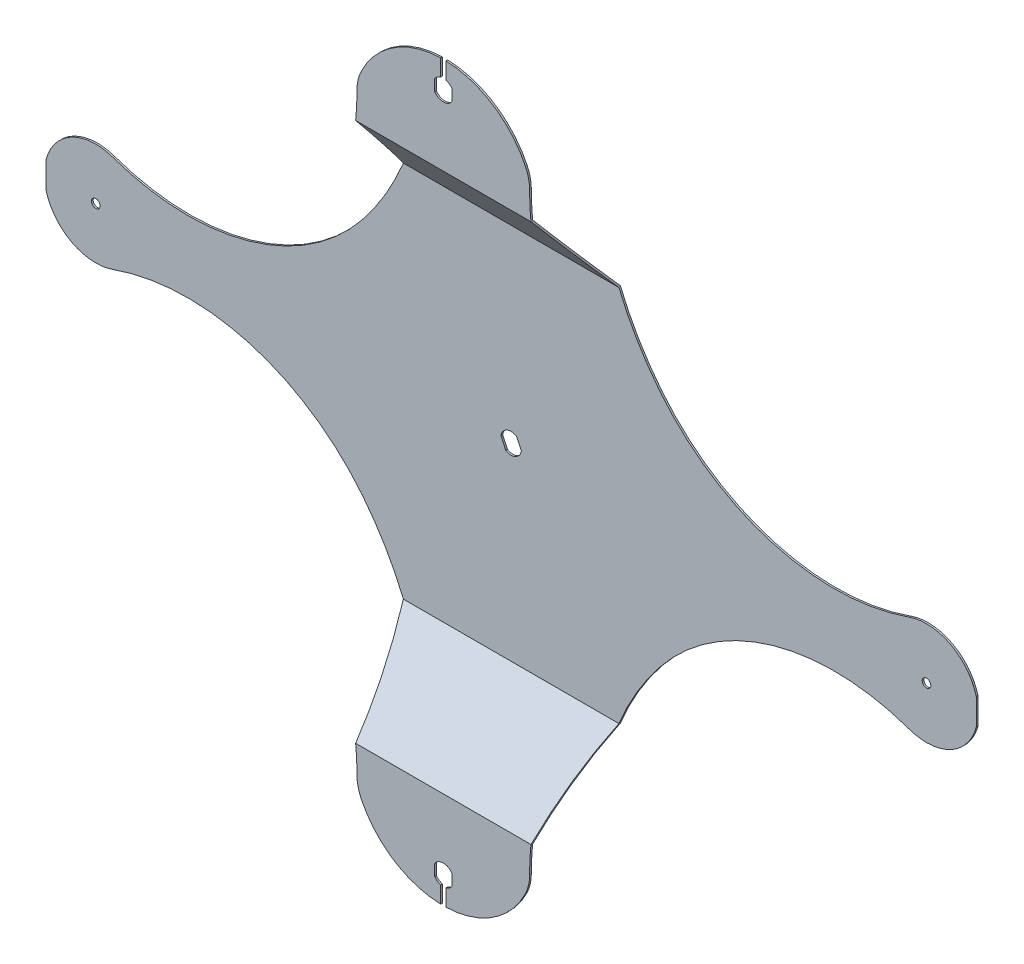
SolidWorks part; units mm, degrees
ref_plane "Alzado" through (0, 0, 0) normal (0, 0, 1) x (1, 0, 0)
ref_plane "Planta" through (0, 0, 0) normal (0, 1, 0) x (1, 0, 0)
ref_plane "Vista lateral" through (0, 0, 0) normal (1, 0, 0) x (0, 0, -1)
sketch "Croquis1" plane through (0, 0, 0) normal (1, 0, 0) x (0, 0, -1)
  line L0 (-18.5, -110) -> (-18.5, 110)
  line L1 (-18.5, 110) -> (-58.0314, 157.1117)
  line L2 (0, 0) -> (-82.8072, 0) construction
  line L3 (-58.0314, 157.1117) -> (-58.0314, 248)
  line L4 (-18.5, -110) -> (-58.0314, -157.1117)
  line L5 (-58.0314, -157.1117) -> (-58.0314, -248)
  line L6 (-57.0314, -157.4757) -> (-57.0314, -248)
  line L7 (-17.5, -110.364) -> (-57.0314, -157.4757)
  line L8 (-17.5, -110.364) -> (-17.5, 110.364)
  line L9 (-17.5, 110.364) -> (-57.0314, 157.4757)
  line L10 (-57.0314, 157.4757) -> (-57.0314, 248)
  line L11 (-58.0314, 248) -> (-57.0314, 248)
  line L12 (-58.0314, -248) -> (-57.0314, -248)
  point P9 (-18.5, 0)
  dimension "D1" = 18.5
  dimension "D2" = 50
  dimension "D3" = 61.5
  dimension "D4" = 110
  dimension "D5" = 496
  dimension "D6" = 1
extrude "Saliente-Extruir1" add sketch "Croquis1" along normal mid plane 542
sketch "Croquis2" plane through (0, 0, 0) normal (0, 0, 1) x (1, 0, 0)
  line L1 (0, 277.0309) -> (0, -277.0309) construction
  line L7 (-271, 213.5) -> (-1.5, 213.5) construction
  line L9 (-300.4496, 0) -> (300.4496, 0) construction
  line L10 (-271, 248) -> (-271, 157.1117) construction
  line L11 (271, 248) -> (271, 157.1117) construction
  line L12 (1.5, 213.5) -> (271, 213.5) construction
  line L13 (1.5, 198) -> (-1.5, 198)
  line L14 (1.5, 198) -> (1.5, 213.5)
  line L31 (-1.5, 198) -> (-1.5, 213.5)
  line L32 (1.5, -198) -> (-1.5, -198)
  line L33 (-1.5, -198) -> (-1.5, -213.5)
  line L34 (1.5, -198) -> (1.5, -213.5)
  line L36 (-300.4496, 277.0309) -> (300.4496, 277.0309)
  line L37 (-300.4496, 277.0309) -> (-300.4496, -277.0309)
  line L38 (-300.4496, -277.0309) -> (300.4496, -277.0309)
  line L39 (300.4496, 277.0309) -> (300.4496, -277.0309)
  line L40 (-300.4496, 277.0309) -> (300.4496, -277.0309) construction
  line L41 (-300.4496, -277.0309) -> (300.4496, 277.0309) construction
  circle A9 centre (0, 0) radius 247.5 construction
  arc A10 (-231.9486, 28.266) -> (-231.9486, -28.266) centre (-242, 0) ccw
  circle A11 centre (0, 0) radius 111.12 construction
  arc A13 (-1.5, 213.4272) -> (1.5, 213.4272) centre (0, 198) ccw construction
  arc A14 (-1.5, 213.5) -> (-47.85, 183.5) centre (0.0101, 160.3615) ccw
  circle A15 centre (0, 198) radius 50 construction
  arc A16 (-47.85, 183.5) -> (-50.3, 172.84) centre (-25.7251, 172.8035) ccw
  arc A17 (-50.3, 172.84) -> (-86.6952, 69.5097) centre (-215.8799, 173.0861) cw
  arc A18 (-231.9486, 28.266) -> (-86.6952, 69.5097) centre (-188.3108, 150.982) ccw
  arc A19 (-231.9486, -28.266) -> (-86.6952, -69.5097) centre (-188.3108, -150.982) cw
  arc A20 (-50.3, -172.84) -> (-86.6952, -69.5097) centre (-215.8799, -173.0861) ccw
  arc A21 (-47.85, -183.5) -> (-50.3, -172.84) centre (-25.7251, -172.8035) cw
  arc A22 (-1.5, -213.5) -> (-47.85, -183.5) centre (0.0101, -160.3615) cw
  arc A23 (47.85, 183.5) -> (50.3, 172.84) centre (25.7251, 172.8035) cw
  arc A24 (47.85, -183.5) -> (50.3, -172.84) centre (25.7251, -172.8035) ccw
  arc A25 (1.5, -213.5) -> (47.85, -183.5) centre (-0.0101, -160.3615) ccw
  arc A26 (50.3, -172.84) -> (86.6952, -69.5097) centre (215.8799, -173.0861) cw
  arc A27 (231.9486, -28.266) -> (86.6952, -69.5097) centre (188.3108, -150.982) ccw
  arc A28 (231.9486, 28.266) -> (231.9486, -28.266) centre (242, 0) cw
  arc A29 (231.9486, 28.266) -> (86.6952, 69.5097) centre (188.3108, 150.982) cw
  arc A30 (50.3, 172.84) -> (86.6952, 69.5097) centre (215.8799, 173.0861) ccw
  arc A31 (1.5, 213.5) -> (47.85, 183.5) centre (-0.0101, 160.3615) cw
  point P6 (0, 0)
  point P7 (0, 0)
  point P24 (0, 198)
  dimension "D1" = 495
  dimension "D3" = 60
  dimension "D9" = 198
  dimension "D4" = 222.24
  dimension "D6" = 31
  dimension "D10" = 47.85
  dimension "D5" = 100
  dimension "D7" = 3
  dimension "D11" = 50.3
  dimension "D13" = 53.16
  dimension "D2" = 242
  dimension "D8" = 30
  dimension "D12" = 40.66
sketch "Croquis4" plane through (0, 0, 0) normal (0, 0, 1) x (1, 0, 0)
  line L0 (-326.6263, 0) -> (326.6263, 0) construction
  line L1 (0, 278.5393) -> (0, -278.5393) construction
  line L2 (-5, -194.6834) -> (5, -201.3166) construction
  line L3 (-5, 201.3166) -> (5, 201.3166) construction
  line L4 (-5, 201.3166) -> (-5, 194.6834)
  line L5 (-5, 194.6834) -> (5, 194.6834) construction
  line L6 (5, 201.3166) -> (5, 194.6834)
  line L7 (-5, 201.3166) -> (5, 194.6834) construction
  line L8 (-5, 194.6834) -> (5, 201.3166) construction
  line L9 (-5, -201.3166) -> (5, -194.6834) construction
  line L10 (-5, -194.6834) -> (5, -194.6834) construction
  line L11 (-5, -201.3166) -> (5, -201.3166) construction
  line L12 (5, -201.3166) -> (5, -194.6834)
  line L13 (-5, -201.3166) -> (-5, -194.6834)
  line L26 (-5.9332, 0.8928) -> (3.1299, 5.119) construction
  line L27 (-5.9332, 0.8928) -> (-3.1299, -5.119)
  line L28 (3.1299, 5.119) -> (5.9332, -0.8928)
  line L29 (-3.1299, -5.119) -> (5.9332, -0.8928) construction
  line L30 (0, 0) -> (-1.4017, 3.0059) construction
  arc A0 (-5, 194.6834) -> (5, 194.6834) centre (0, 198) ccw
  arc A1 (-3.1299, -5.119) -> (5.9332, -0.8928) centre (0, 0) ccw
  arc A4 (5, 201.3166) -> (-5, 201.3166) centre (0, 198) ccw
  arc A5 (5, -201.3166) -> (-5, -201.3166) centre (0, -198) cw
  arc A6 (-5, -194.6834) -> (5, -194.6834) centre (0, -198) cw
  circle A7 centre (-242, 0) radius 2.5
  arc A10 (3.1299, 5.119) -> (-5.9332, 0.8928) centre (0, 0) ccw
  circle A11 centre (242, 0) radius 2.5
  point P4 (0, 0)
  point P8 (0, 0)
  dimension "D4" = 10
  dimension "D5" = 12
  dimension "D6" = 12
  dimension "D2" = 5
  dimension "D1" = 198
  dimension "D8" = 10
  dimension "D9" = 25
extrude "Cortar-Extruir9" cut sketch "Croquis4" against normal through all both and the other way through all
extrude "Cortar-Extruir10" cut sketch "Croquis2" against normal through all both and the other way through all contours L39 L36 L37 L38 L14 A31 A23 A30 A29 A28 A27 A26 A24 A25 L34 L32 L33 A22 A21 A20 A19 A10 A18 A17 A16 A14 L31 L13
